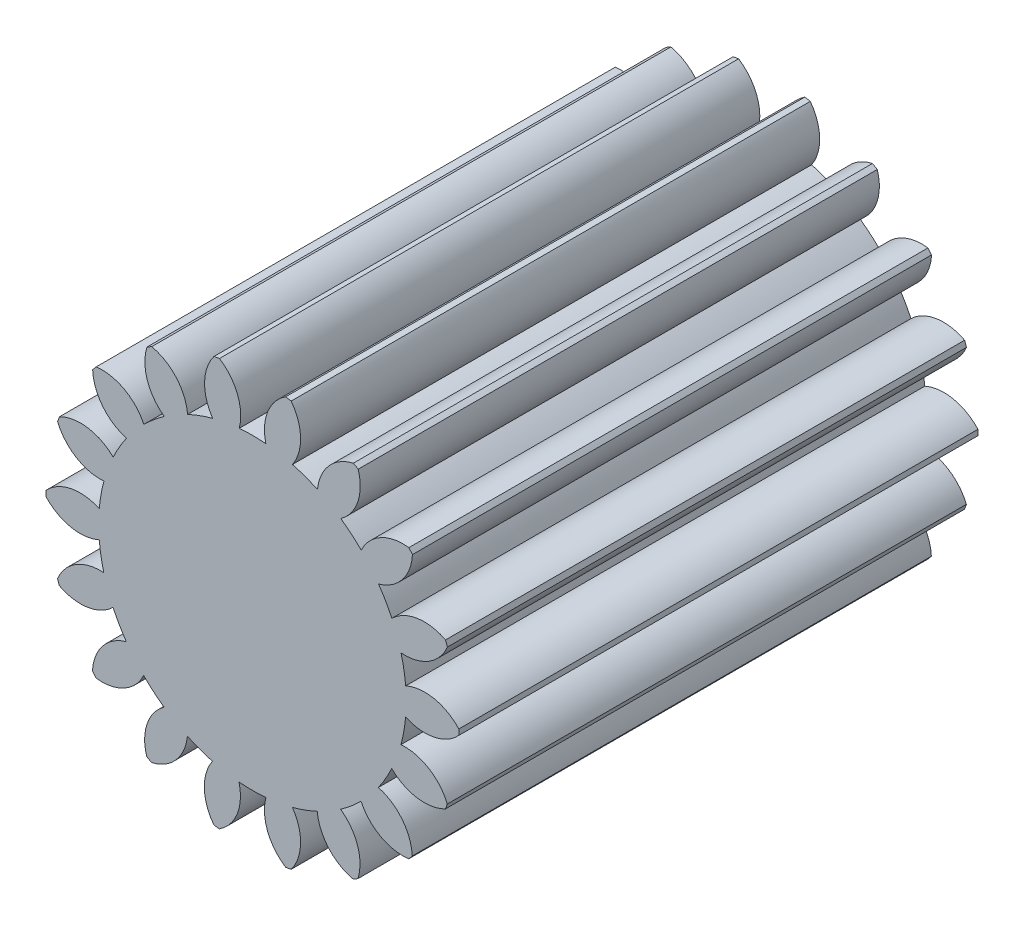
SolidWorks part; units mm, degrees
ref_plane "Ön Düzlem" through (0, 0, 0) normal (0, 0, 1) x (1, 0, 0)
ref_plane "Üst Düzlem" through (0, 0, 0) normal (0, 1, 0) x (1, 0, 0)
ref_plane "Sağ Düzlem" through (0, 0, 0) normal (1, 0, 0) x (0, 0, -1)
sketch "Sketch4" plane through (0, 0, 0) normal (0, 0, 1) x (1, 0, 0)
  line L1 (4.969, 0.1208) -> (5.2505, 1.7176)
  line L37 (11.901, 0.1208) -> (11.68, 1.374)
  line L38 (8.435, 19.7016) -> (7.2978, 13.3283) construction
  line L39 (8.435, 19.7016) -> (5.1866, 14.1016) construction
  arc A1 (5.2335, 0.0769) -> (7.1393, 4.9478) centre (2.8101, 3.8334) ccw
  arc A2 (4.7054, 0.17) -> (5.2335, 0.0769) centre (7.2978, 13.3283) ccw
  arc A3 (4.5805, 5.399) -> (4.7054, 0.17) centre (8.2675, 2.8711) ccw
  arc A4 (12.1646, 0.17) -> (12.2895, 5.399) centre (8.6025, 2.8711) ccw
  arc A5 (11.6365, 0.0769) -> (12.1646, 0.17) centre (9.5722, 13.3283) ccw
  arc A6 (9.7307, 4.9478) -> (11.6365, 0.0769) centre (14.0599, 3.8334) ccw
  arc A7 (4.5805, 5.399) -> (12.2895, 5.399) centre (8.435, 19.7016) ccw
  circle A8 centre (8.435, 19.7016) radius 14.8128
  arc A9 (-0.0788, 7.5799) -> (-1.7499, 2.6235) centre (2.5212, 3.9434) ccw
  arc A10 (-1.2855, 2.3554) -> (2.1714, 6.2807) centre (-2.2779, 6.7142) ccw
  arc A11 (-1.7499, 2.6235) -> (-1.2855, 2.3554) centre (5.1866, 14.1016) ccw
  arc A12 (-3.7113, 11.2228) -> (-6.9767, 7.1369) centre (-2.5117, 6.9164) ccw
  arc A13 (-6.632, 6.7261) -> (-2.0411, 9.2324) centre (-6.0738, 11.1615) ccw
  arc A14 (-6.9767, 7.1369) -> (-6.632, 6.7261) centre (3.4672, 15.5503) ccw
  arc A15 (-5.8786, 15.8884) -> (-10.3446, 13.1657) centre (-6.2243, 11.4314) ccw
  arc A16 (-10.1612, 12.6618) -> (-4.99, 13.4468) centre (-8.1197, 16.6388) ccw
  arc A17 (-10.3446, 13.1657) -> (-10.1612, 12.6618) centre (2.347, 17.4997) ccw
  arc A18 (-6.3196, 21.0139) -> (-11.4475, 19.9829) centre (-8.1688, 16.9439) ccw
  arc A19 (-11.4475, 19.4466) -> (-6.3196, 18.4156) centre (-8.1688, 22.4856) ccw
  arc A20 (-11.4475, 19.9829) -> (-11.4475, 19.4466) centre (1.9611, 19.7148) ccw
  arc A21 (-4.9809, 25.9812) -> (-10.1522, 26.7661) centre (-8.1107, 22.7891) ccw
  arc A22 (-10.3356, 26.2622) -> (-5.8696, 23.5395) centre (-6.2153, 27.9965) ccw
  arc A23 (-10.1522, 26.7661) -> (-10.3356, 26.2622) centre (2.356, 21.9282) ccw
  arc A24 (-2.0241, 30.191) -> (-6.615, 32.6973) centre (-6.0568, 28.2618) ccw
  arc A25 (-6.9597, 32.2865) -> (-3.6943, 28.2005) centre (-2.4948, 32.507) ccw
  arc A26 (-6.615, 32.6973) -> (-6.9597, 32.2865) centre (3.4841, 23.873) ccw
  arc A27 (2.1942, 33.1356) -> (-1.2626, 37.0609) centre (-2.2551, 32.7021) ccw
  arc A28 (-1.727, 36.7928) -> (-0.056, 31.8364) centre (2.5441, 35.4729) ccw
  arc A29 (-1.2626, 37.0609) -> (-1.727, 36.7928) centre (5.2095, 25.3148) ccw
  arc A30 (7.1653, 34.4599) -> (5.2595, 39.3308) centre (2.8361, 35.5743) ccw
  arc A31 (4.7314, 39.2377) -> (4.6064, 34.0087) centre (8.2935, 36.5366) ccw
  arc A32 (5.2595, 39.3308) -> (4.7314, 39.2377) centre (7.3238, 26.0794) ccw
  arc A33 (12.2895, 34.0041) -> (12.1646, 39.2331) centre (8.6025, 36.532) ccw
  arc A34 (11.6365, 39.3262) -> (9.7307, 34.4553) centre (14.0599, 35.5697) ccw
  arc A35 (12.1646, 39.2331) -> (11.6365, 39.3262) centre (9.5722, 26.0749) ccw
  arc A36 (16.9488, 31.8232) -> (18.6199, 36.7796) centre (14.3488, 35.4597) ccw
  arc A37 (18.1555, 37.0477) -> (14.6986, 33.1224) centre (19.1479, 32.6889) ccw
  arc A38 (18.6199, 36.7796) -> (18.1555, 37.0477) centre (11.6834, 25.3016) ccw
  arc A39 (20.5813, 28.1803) -> (23.8467, 32.2663) centre (19.3817, 32.4868) ccw
  arc A40 (23.502, 32.677) -> (18.9111, 30.1708) centre (22.9438, 28.2416) ccw
  arc A41 (23.8467, 32.2663) -> (23.502, 32.677) centre (13.4028, 23.8528) ccw
  arc A42 (22.7486, 23.5147) -> (27.2146, 26.2374) centre (23.0943, 27.9717) ccw
  arc A43 (27.0312, 26.7413) -> (21.86, 25.9564) centre (24.9897, 22.7643) ccw
  arc A44 (27.2146, 26.2374) -> (27.0312, 26.7413) centre (14.523, 21.9034) ccw
  arc A45 (23.1896, 18.3892) -> (28.3175, 19.4202) centre (25.0388, 22.4592) ccw
  arc A46 (28.3175, 19.9565) -> (23.1896, 20.9875) centre (25.0388, 16.9176) ccw
  arc A47 (28.3175, 19.4202) -> (28.3175, 19.9565) centre (14.9089, 19.6884) ccw
  arc A48 (21.8509, 13.422) -> (27.0222, 12.637) centre (24.9807, 16.614) ccw
  arc A49 (27.2056, 13.1409) -> (22.7396, 15.8636) centre (23.0853, 11.4066) ccw
  arc A50 (27.0222, 12.637) -> (27.2056, 13.1409) centre (14.514, 17.4749) ccw
  arc A51 (18.8941, 9.2122) -> (23.485, 6.7059) centre (22.9268, 11.1413) ccw
  arc A52 (23.8297, 7.1166) -> (20.5643, 11.2026) centre (19.3648, 6.8961) ccw
  arc A53 (23.485, 6.7059) -> (23.8297, 7.1166) centre (13.3859, 15.5301) ccw
  arc A54 (14.6758, 6.2675) -> (18.1326, 2.3422) centre (19.1251, 6.701) ccw
  arc A55 (18.597, 2.6103) -> (16.926, 7.5667) centre (14.3259, 3.9302) ccw
  arc A56 (18.1326, 2.3422) -> (18.597, 2.6103) centre (11.6605, 14.0884) ccw
  point P12 (3.125, 3.3641)
  point P15 (3.125, 3.3641)
  point P44 (11.7482, 0.9873)
  point P45 (5.1218, 0.9873)
  dimension "D2" = 20
  dimension "D3" = 17
  dimension "D6" = 20
extrude "Boss-Extrude1" add sketch "Sketch4" along normal blind 50
sketch "Sketch5" plane through (0, 0, 50) normal (0, 0, 1) x (1, 0, 0)
  circle A0 centre (8.435, 19.7016) radius 14.8128
